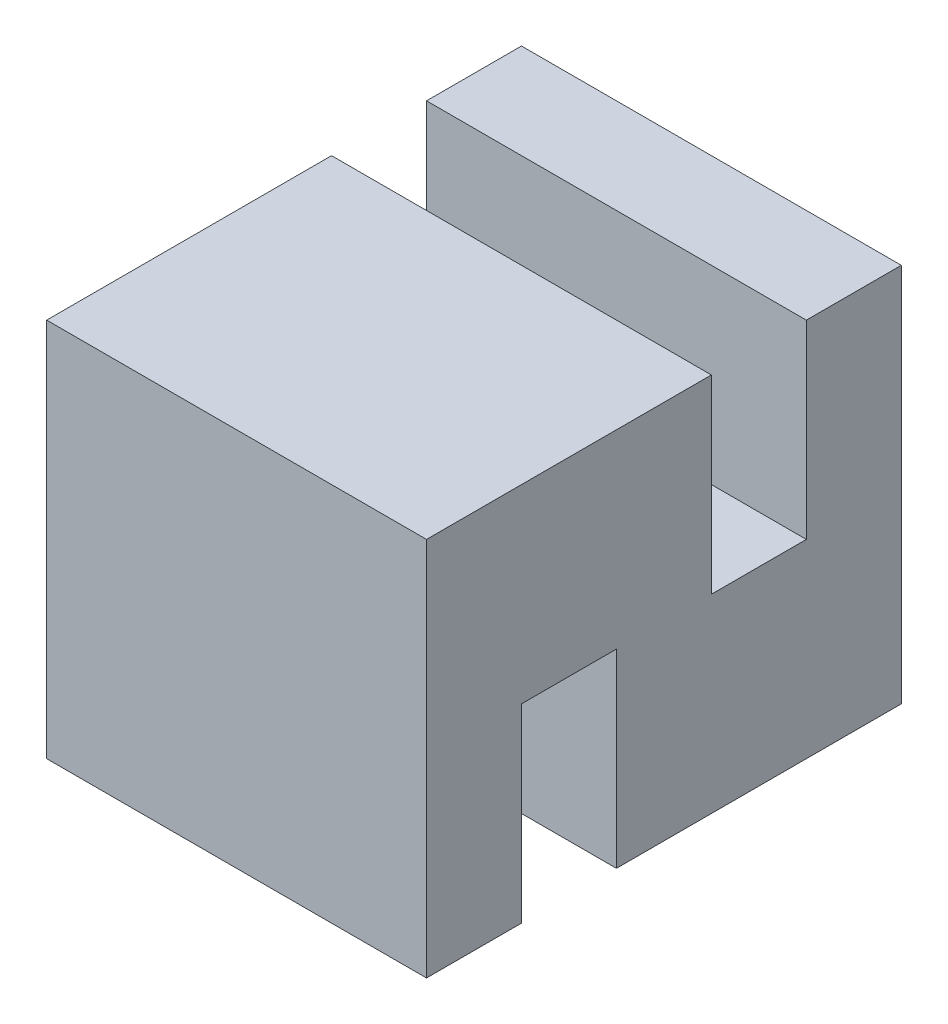
SolidWorks part; units mm, degrees
ref_plane "Front Plane" through (0, 0, 0) normal (0, 0, 1) x (1, 0, 0)
ref_plane "Top Plane" through (0, 0, 0) normal (0, 1, 0) x (1, 0, 0)
ref_plane "Right Plane" through (0, 0, 0) normal (1, 0, 0) x (0, 0, -1)
sketch "Sketch1" plane through (0, 0, 0) normal (0, 0, 1) x (1, 0, 0)
  line L0 (6, -4.5) -> (-6, -4.5) construction
  line L1 (-3, 1.5) -> (3, 1.5)
  line L2 (-3, 1.5) -> (-3, -4.5)
  line L3 (-3, -4.5) -> (3, -4.5)
  line L4 (3, 1.5) -> (3, -4.5)
  point P5 (0, 0)
extrude "Boss-Extrude1" add sketch "Sketch1" along normal blind 1.5
sketch "Sketch2" plane through (0, 0, 0) normal (0, 0, -1) x (-1, 0, 0)
  line L0 (3, -1.5) -> (-3, -1.5) construction
  line L1 (-3, 1.5) -> (3, 1.5)
  line L2 (-3, 1.5) -> (-3, -1.5)
  line L3 (-3, -1.5) -> (3, -1.5)
  line L4 (3, 1.5) -> (3, -1.5)
  point P4 (0, 0)
  point P6 (0, 0)
extrude "Boss-Extrude2" add sketch "Sketch2" along normal up to surface (1.5 mm away)
sketch "Sketch3" plane through (0, 0, -1.5) normal (0, 0, -1) x (-1, 0, 0)
  line L4 (3, 1.5) -> (-3, 1.5)
  line L5 (-3, 1.5) -> (-3, -4.5)
  line L6 (-3, -4.5) -> (3, -4.5)
  line L7 (3, -4.5) -> (3, 1.5)
  line L8 (3, 1.5) -> (-3, 1.5)
  line L9 (-3, 1.5) -> (-3, -4.5)
  line L10 (-3, -4.5) -> (3, -4.5)
  line L11 (3, -4.5) -> (3, 1.5)
  dimension "D1" = 0
extrude "Boss-Extrude4" add sketch "Sketch3" along normal blind 1.5
sketch "Sketch4" plane through (0, 0, -3) normal (0, 0, -1) x (-1, 0, 0)
  line L1 (-3, -4.5) -> (3, -4.5)
  line L2 (-3, -4.5) -> (-3, -1.5)
  line L3 (-3, -1.5) -> (3, -1.5)
  line L4 (3, -4.5) -> (3, -1.5)
  line L5 (-3, -1.5) -> (3, -1.5) construction
  line L6 (-3, -1.5) -> (3, -1.5) construction
  point P5 (0, 0)
  point P9 (0, 0)
extrude "Boss-Extrude5" add sketch "Sketch4" along normal blind 1.5
sketch "Sketch5" plane through (0, 0, -4.5) normal (0, 0, -1) x (-1, 0, 0)
  line L4 (3, 1.5) -> (-3, 1.5)
  line L5 (-3, 1.5) -> (-3, -4.5)
  line L6 (-3, -4.5) -> (3, -4.5)
  line L7 (3, -4.5) -> (3, 1.5)
  line L8 (3, 1.5) -> (-3, 1.5)
  line L9 (-3, 1.5) -> (-3, -4.5)
  line L10 (-3, -4.5) -> (3, -4.5)
  line L11 (3, -4.5) -> (3, 1.5)
  dimension "D1" = 0
extrude "Boss-Extrude6" add sketch "Sketch5" along normal blind 1.5
